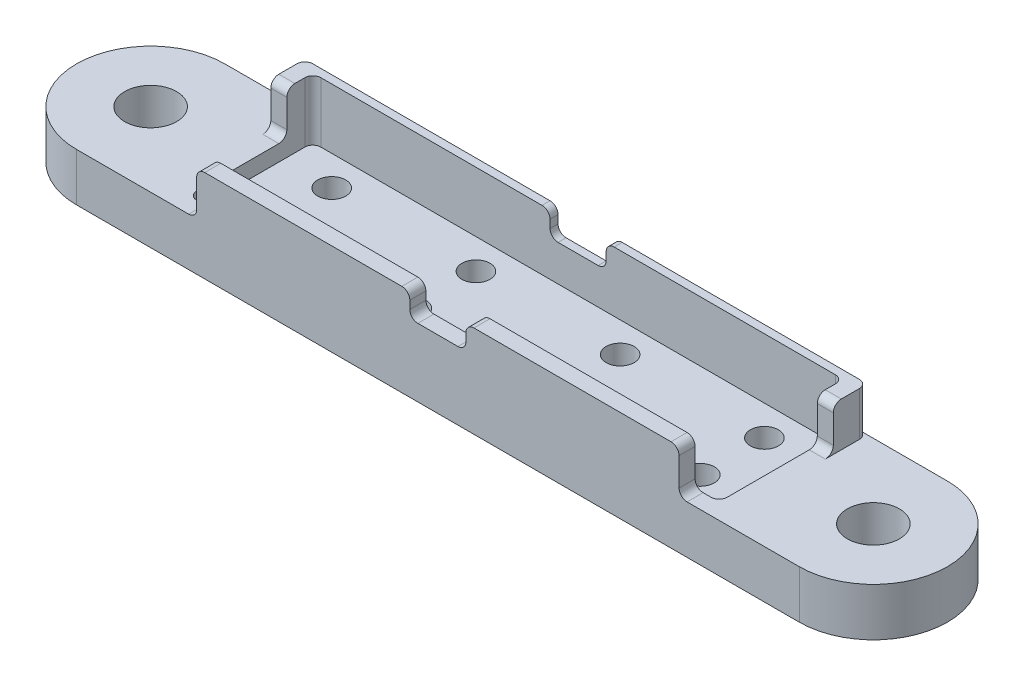
SolidWorks part; units mm, degrees
material "Delrin 2700 NC010, Low Viscosity Acetal Copolymer (SS)"
ref_plane "Front Plane" through (0, 0, 0) normal (0, 0, 1) x (1, 0, 0)
ref_plane "Top Plane" through (0, 0, 0) normal (0, 1, 0) x (1, 0, 0)
ref_plane "Right Plane" through (0, 0, 0) normal (1, 0, 0) x (0, 0, -1)
sketch "Sketch1" plane through (0, 0, 0) normal (0, 1, 0) x (1, 0, 0)
  line L1 (-35.1, -9.25) -> (0, -9.25)
  line L2 (-35.1, -9.25) -> (-35.1, 9.25)
  line L3 (-35.1, 9.25) -> (0, 9.25)
  line L4 (0, -9.25) -> (0, 9.25)
  line L5 (-35.1, -9.25) -> (0, 9.25) construction
  line L6 (-35.1, 9.25) -> (0, -9.25) construction
  point P0 (-17.55, 0)
  point P8 (0, 0)
  dimension "D1" = 35.1
  dimension "D2" = 18.5
extrude "Boss-Extrude1" add sketch "Sketch1" along normal blind 11.5
shell "Shell1" [suppressed] thickness 1
sketch "Sketch7" plane through (0, 11.5, 0) normal (0, 1, 0) x (1, 0, 0)
  line L0 (0, -9.25) -> (0, 9.25) construction
  line L1 (0, -7.25) -> (-33.1, -7.25)
  line L2 (0, -7.25) -> (0, 8.25)
  line L3 (0, 8.25) -> (-33.1, 8.25)
  line L4 (-33.1, -7.25) -> (-33.1, 8.25)
  line L5 (-35.1, -9.25) -> (0, -9.25) construction
  line L6 (0, 9.25) -> (-35.1, 9.25) construction
  line L7 (-35.1, 9.25) -> (-35.1, -9.25) construction
  dimension "D1" = 2
  dimension "D2" = 1
  dimension "D3" = 2
extrude "Cut-Extrude5" cut sketch "Sketch7" against normal offset from surface (7.5 mm away) 4 up to face at (-17.55, 0, 0)
sketch "Sketch2" plane through (0, 0, 0) normal (0, 1, 0) x (-1, 0, 0)
  line L0 (27, 3.5) -> (9, 3.5) construction
  line L2 (27, 3.5) -> (27, -4.5) construction
  line L3 (27, -4.5) -> (9, -4.5) construction
  line L4 (9, -4.5) -> (9, 3.5) construction
  line L5 (27, -0.5) -> (18.8977, -0.5) construction
  line L6 (17.55, -9.25) -> (17.55, 9.25) construction
  line L7 (0, 7.25) -> (0, -8.25) construction
  line L8 (27, -0.5) -> (0, -0.5) construction
  line L9 (0, -9.25) -> (35.1, -9.25) construction
  line L10 (35.1, 9.25) -> (0, 9.25) construction
  circle A0 centre (27, 3.5) radius 1.75
  circle A1 centre (9, 3.5) radius 1.75
  circle A2 centre (27, -4.5) radius 1.75
  circle A3 centre (9, -4.5) radius 1.75
  circle A5 centre (27, 3.5) radius 2.5 construction
  circle A6 centre (27, -4.5) radius 2.5 construction
  circle A7 centre (9, -4.5) radius 2.5 construction
  circle A8 centre (9, 3.5) radius 2.5 construction
  dimension "D1" = 3.5
  dimension "D4" = 9
  dimension "D5" = 5
  dimension "D2" = 18
  dimension "D3" = 8
extrude "Cut-Extrude1" cut sketch "Sketch2" along normal through all
sketch "Sketch3" [suppressed] plane through (0, 5, 0) normal (0, 1, 0) x (1, 0, 0)
  line L1 (-2.9573, -5.1559) -> (2.9865, -5.139)
  line L2 (2.9865, -5.139) -> (5.9438, 0.0169)
  line L3 (5.9438, 0.0169) -> (2.9573, 5.1559)
  line L4 (2.9573, 5.1559) -> (-2.9865, 5.139)
  line L5 (-2.9865, 5.139) -> (-5.9438, -0.0169)
  line L6 (-5.9438, -0.0169) -> (-2.9573, -5.1559)
  circle A0 centre (0, 0) radius 2.6 construction
  circle A1 centre (0, 0) radius 5.1475 construction
  dimension "D1" = 5.2
extrude "Cut-Extrude2" [suppressed] cut sketch "Sketch3" against normal blind 0.5
sketch "Sketch4" plane through (-35.1, 0, 0) normal (-1, 0, 0) x (0, 0, 1)
  line L0 (-9.25, 11.5) -> (9.25, 11.5) construction
  line L1 (-5, 11.5) -> (9.25, 11.5)
  line L3 (-5, 6) -> (9.25, 6)
  line L4 (9.25, 11.5) -> (9.25, 6)
  line L5 (0, 6) -> (0, 0) construction
  line L11 (-9.25, 0) -> (9.25, 0) construction
  line L12 (-5, 6) -> (-5, 11.5)
  dimension "D1" = 5
  dimension "D2" = 5.5
extrude "Cut-Extrude3" cut sketch "Sketch4" against normal offset from surface (5 mm away) 3 up to face at (-33.1, 7.75, -0.5) offset beyond the face yes
sketch "Sketch8" plane through (0, 0, 0) normal (0, -1, 0) x (-1, 0, 0)
  line L0 (35.1, -9.25) -> (45.1, -9.25)
  line L1 (35.1, 9.25) -> (45.1, 9.25)
  line L2 (35.1, 9.25) -> (35.1, -9.25)
  arc A0 (45.1, 9.25) -> (45.1, -9.25) centre (45.1, 0) cw
  circle A1 centre (45.1, 0) radius 3.25
  dimension "D2" = 6.5
  dimension "D1" = 10
extrude "bolt extrude" add sketch "Sketch8" against normal blind 6
mirror "Mirror1" about plane through (0, 0, 0) normal (1, 0, 0) of bodies 112 105
sketch "Sketch5" plane through (0, 0, 0) normal (0, 1, 0) x (1, 0, 0)
  line L0 (33.1, 0.5) -> (0, 0.5) construction
  line L1 (33.1, 8.25) -> (33.1, -7.25) construction
  line L4 (0, 0.5) -> (0, 0) construction
  circle A0 centre (0, 0.5) radius 2.75
  dimension "D1" = 5.5
extrude "Cut-Extrude4" [suppressed] cut sketch "Sketch5" along normal through all
sketch "Sketch6" [suppressed] plane through (0, 4, 0) normal (0, 1, 0) x (1, 0, 0)
  circle A0 centre (0, 0.5) radius 6.25
  circle A1 centre (0, 0.5) radius 5.25
  circle A2 centre (0, 0.5) radius 2.75 construction
  dimension "D1" = 10.5
  dimension "D2" = 1
extrude "Boss-Extrude2" [suppressed] add sketch "Sketch6" along normal blind 3.5
fillet "Fillet3" radius 1 8 edges at (-34.1, 6, -5) (-34.1, 11.5, -5) (-30.1, 11.5, 8.25) (-30.1, 6, 8.25) (34.1, 11.5, -5) (34.1, 6, -5) (30.1, 11.5, 8.25) (30.1, 6, 8.25)
fillet "Fillet4" [suppressed] radius 0.5
fillet "Fillet5" [suppressed] radius 0.5
sketch "Sketch9" plane through (0, 11.5, 0) normal (0, 1, 0) x (1, 0, 0)
  line L0 (35.1, 9.25) -> (-35.1, 9.25) construction
  line L1 (-3.5, 9.25) -> (3.5, 9.25)
  line L2 (-3.5, 9.25) -> (-3.5, -9.25)
  line L3 (-3.5, -9.25) -> (3.5, -9.25)
  line L4 (3.5, 9.25) -> (3.5, -9.25)
  line L5 (-29.1, -9.25) -> (29.1, -9.25) construction
  dimension "D1" = 3.5
  dimension "D2" = 3.5
extrude "Cut-Extrude6" cut sketch "Sketch9" against normal blind 3
fillet "Fillet6" radius 1 14 edges at (-33.1, 7.75, -8.25) (-33.1, 5, 7.25) (-3.5, 8.5, -8.75) (-3.5, 8.5, 8.25) (3.5, 8.5, -8.75) (3.5, 8.5, 8.25) (-3.5, 11.5, -8.75) (3.5, 11.5, -8.75) (3.5, 11.5, 8.25) (-3.5, 11.5, 8.25) (-35.1, 8.75, -9.25) (35.1, 8.75, -9.25) (33.1, 7.75, -8.25) (33.1, 5, 7.25)
fillet "Fillet7" [suppressed] radius 1
fillet "Fillet8" [suppressed] radius 1
